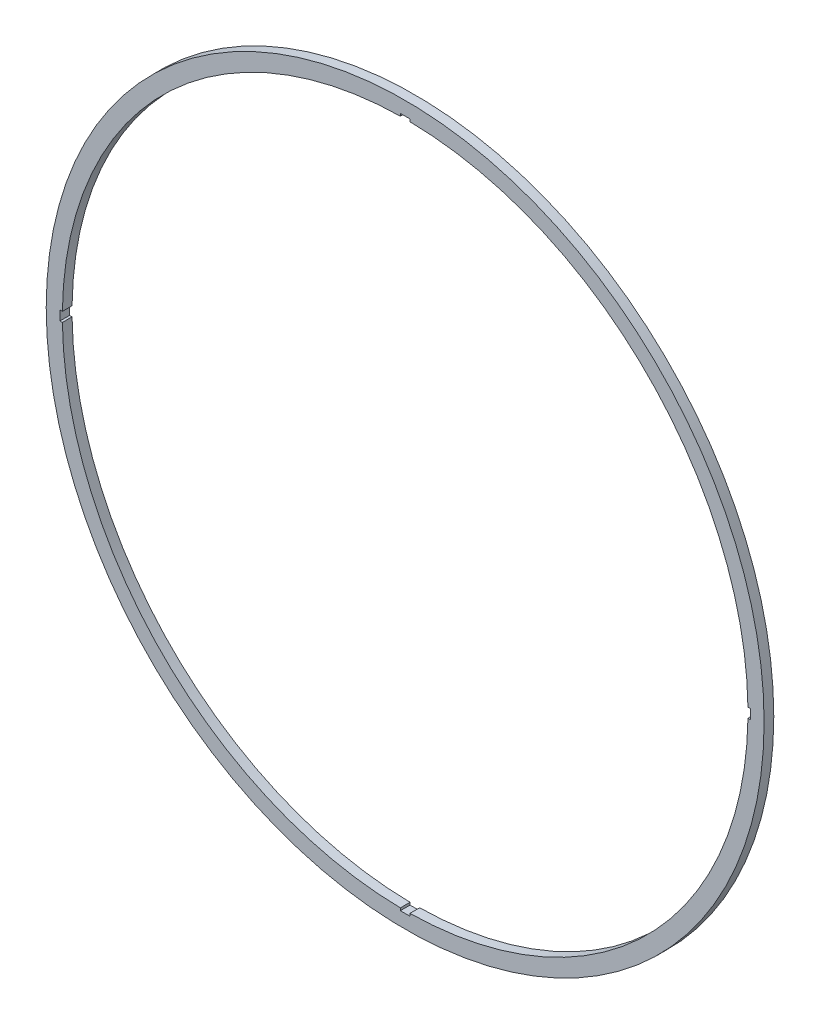
SolidWorks part; units mm, degrees
ref_plane "Front Plane" through (0, 0, 0) normal (0, 0, 1) x (1, 0, 0)
ref_plane "Top Plane" through (0, 0, 0) normal (0, 1, 0) x (1, 0, 0)
ref_plane "Right Plane" through (0, 0, 0) normal (1, 0, 0) x (0, 0, -1)
sketch "Sketch1" plane through (0, 0, 0) normal (0, 0, 1) x (1, 0, 0)
  line L0 (0, 0) -> (0, 484.7894) construction
  line L1 (428.0005, 5.9302) -> (424.9586, 5.9302)
  line L2 (-5.9302, 428.0005) -> (5.9302, 428.0005)
  line L3 (-5.9302, 428.0005) -> (-5.9302, 424.9586)
  line L5 (5.9302, 428.0005) -> (5.9302, 424.9586)
  line L6 (-5.9302, 428.0005) -> (0, 425) construction
  line L7 (0, 425) -> (5.9302, 428.0005) construction
  line L8 (428.0005, 5.9302) -> (428.0005, -5.9302)
  line L9 (428.0005, -5.9302) -> (424.9586, -5.9302)
  line L10 (5.9302, -428.0005) -> (5.9302, -424.9586)
  line L11 (5.9302, -428.0005) -> (-5.9302, -428.0005)
  line L12 (-5.9302, -428.0005) -> (-5.9302, -424.9586)
  line L13 (-428.0005, -5.9302) -> (-424.9586, -5.9302)
  line L14 (-428.0005, -5.9302) -> (-428.0005, 5.9302)
  line L15 (-428.0005, 5.9302) -> (-424.9586, 5.9302)
  circle A0 centre (0, 0) radius 445
  arc A1 (-5.9302, 424.9586) -> (-424.9586, 5.9302) centre (0, 0) ccw
  arc A2 (424.9586, 5.9302) -> (5.9302, 424.9586) centre (0, 0) ccw
  circle A3 centre (0, 0) radius 425 construction
  arc A4 (5.9302, -424.9586) -> (424.9586, -5.9302) centre (0, 0) ccw
  arc A5 (-424.9586, -5.9302) -> (-5.9302, -424.9586) centre (0, 0) ccw
  point P5 (0, 425)
  point P7 (430, 0)
  dimension "D1" = 20
  dimension "D3" = 890
  dimension "D2" = 4
extrude "Boss-Extrude1" add sketch "Sketch1" along normal blind 12
